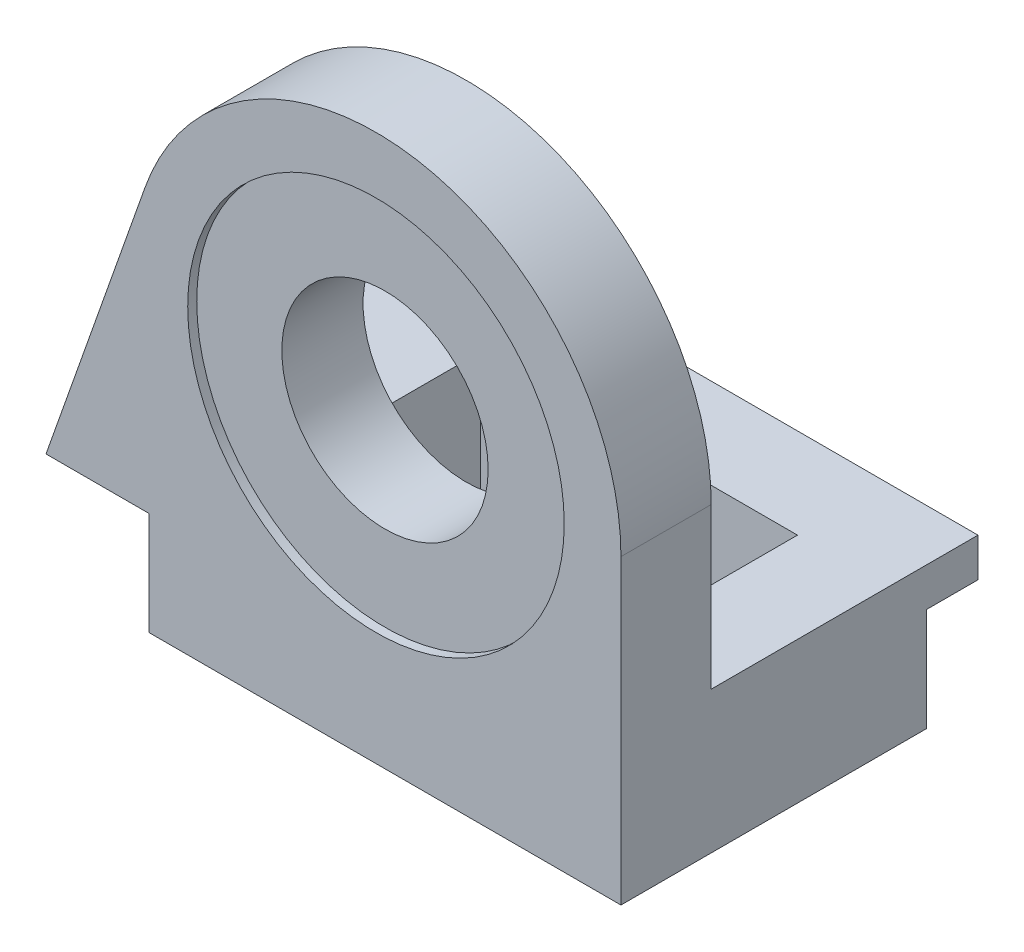
SolidWorks part; units mm, degrees
ref_plane "Front" through (0, 0, 0) normal (0, 0, 1) x (1, 0, 0)
ref_plane "Top" through (0, 0, 0) normal (0, 1, 0) x (1, 0, 0)
ref_plane "Right" through (0, 0, 0) normal (1, 0, 0) x (0, 0, -1)
sketch "Sketch1" plane through (0, 0, 0) normal (0, 0, 1) x (1, 0, 0)
  line L0 (-95, 0) -> (-95, -77) construction
  line L1 (-127.95, -117) -> (-87.95, -117) construction
  line L2 (-127.95, -117) -> (-127.95, -77) construction
  line L3 (-95, -77) -> (-87.95, -77)
  line L4 (-87.95, -95) -> (-87.95, -77)
  line L5 (-127.95, -117) -> (-87.95, -77) construction
  line L6 (-127.95, -77) -> (-87.95, -117) construction
  line L7 (95, 0) -> (95, -95)
  line L8 (95, -95) -> (0, -95) construction
  line L9 (0, -95) -> (-87.95, -95) construction
  line L10 (-95, -77) -> (-127.95, -77) construction
  line L11 (-87.95, -95) -> (-87.95, -117) construction
  line L12 (-95, -77) -> (-127.95, -77)
  line L13 (-127.95, -77) -> (-89.5763, 31.64)
  line L14 (-95, -77) -> (-127.95, -77)
  line L15 (-87.95, -95) -> (-87.95, -117)
  line L16 (-87.95, -117) -> (95, -117)
  line L17 (95, -117) -> (95, -95)
  arc A0 (95, 0) -> (-89.5763, 31.64) centre (0, 0) ccw
  point P7 (-107.95, -97)
  dimension "D1" = 190
  dimension "D5" = 87.95
  dimension "D2" = 40
  dimension "D3" = 40
  dimension "D4" = 77
extrude "Boss-Extrude1" add sketch "Sketch1" along normal blind 35 contours L7 A0 L13 L12 L3 L4 L9 L8
sketch "Sketch2" plane through (0, 0, 0) normal (0, 0, -1) x (-1, 0, 0)
  line L0 (127.95, -77) -> (122.6517, -62)
  line L1 (87.95, -117) -> (62.95, -117)
  line L2 (87.95, -117) -> (87.95, -77)
  line L3 (88.9771, -62) -> (62.95, -62)
  line L4 (62.95, -117) -> (62.95, -62)
  line L5 (87.95, -117) -> (62.95, -62) construction
  line L6 (88.9771, -62) -> (62.95, -117) construction
  line L7 (88.9771, -62) -> (122.6517, -62)
  line L9 (87.95, -77) -> (127.95, -77)
  line L11 (88.9771, -62) -> (127.95, -77) construction
  line L12 (87.95, -77) -> (123.526, -64.4751) construction
  line L13 (127.95, -77) -> (89.5763, 31.64) construction
  line L15 (-95, -117) -> (-60, -117)
  line L16 (-95, -117) -> (-95, -62)
  line L17 (-95, -62) -> (-60, -62)
  line L18 (-60, -117) -> (-60, -62)
  line L19 (-95, -117) -> (-60, -62) construction
  line L20 (-95, -62) -> (-60, -117) construction
  point P4 (75.7016, -90.0535)
  point P9 (108.8408, -69.6452)
  point P18 (-77.5, -89.5)
  dimension "D1" = 25
  dimension "D2" = 15
  dimension "D3" = 35
  dimension "D4" = 55
extrude "Boss-Extrude2" add sketch "Sketch2" along normal blind 83.45
sketch "Sketch3" plane through (0, 0, -83.45) normal (0, 0, -1) x (-1, 0, 0)
  line L0 (127.95, -77) -> (-95, -77)
  line L1 (-95, -62) -> (-95, -117) construction
  line L2 (-95, -77) -> (-95, -62)
  line L3 (-95, -62) -> (122.6517, -62)
  line L4 (122.6517, -62) -> (127.95, -77)
extrude "Boss-Extrude3" add sketch "Sketch3" along normal blind 20
sketch "Sketch4" plane through (0, -62, 0) normal (0, 1, 0) x (1, 0, 0)
  line L0 (60, 83.45) -> (60, 0) construction
  line L1 (-62.95, 83.45) -> (60, 83.45)
  line L2 (-62.95, 83.45) -> (-62.95, 68.45)
  line L3 (-62.95, 68.45) -> (60, 68.45)
  line L4 (60, 83.45) -> (60, 68.45)
  line L5 (-62.95, 83.45) -> (60, 68.45) construction
  line L6 (-62.95, 68.45) -> (60, 83.45) construction
  point P4 (-1.475, 75.95)
  dimension "D1" = 15
extrude "Boss-Extrude4" add sketch "Sketch4" against normal up to surface (55 mm away) up to face at (1.025, -117, -32.975)
sketch "Sketch5" plane through (0, 0, 35) normal (0, 0, 1) x (1, 0, 0)
  circle A0 centre (0, 0) radius 73
  dimension "D1" = 146
extrude "Cut-Extrude1" cut sketch "Sketch5" against normal blind 3.5
sketch "Sketch6" plane through (0, 0, 31.5) normal (0, 0, 1) x (1, 0, 0)
  circle A0 centre (0, 0) radius 40
  dimension "D1" = 80
extrude "Cut-Extrude2" cut sketch "Sketch6" against normal up to next
